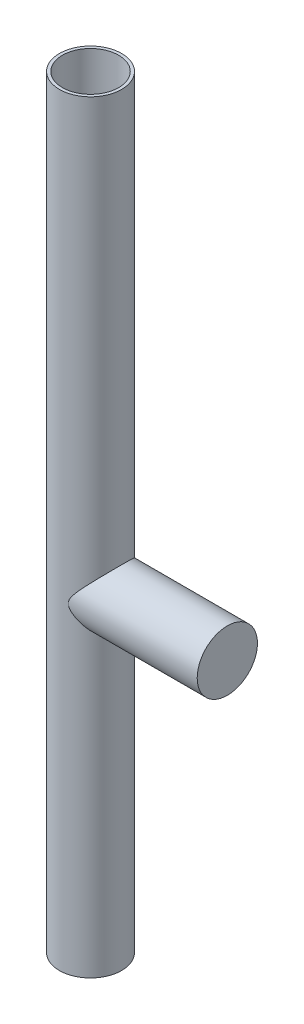
SolidWorks part; units mm, degrees
ref_plane "Front Plane" through (0, 0, 0) normal (0, 0, 1) x (1, 0, 0)
ref_plane "Top Plane" through (0, 0, 0) normal (0, 1, 0) x (1, 0, 0)
ref_plane "Right Plane" through (0, 0, 0) normal (1, 0, 0) x (0, 0, -1)
sketch "Sketch1" plane through (0, 0, 0) normal (0, 1, 0) x (1, 0, 0)
  circle A0 centre (0, 0) radius 7.75
  circle A1 centre (0, 0) radius 7
  dimension "D1" = 15.5
  dimension "D2" = 14
extrude "Boss-Extrude1" add sketch "Sketch1" along normal blind 160 and the other way blind 5
sketch "Sketch5" plane through (0, 0, 0) normal (1, 0, 0) x (0, 0, -1)
  circle A0 centre (0, 75) radius 7.5
  dimension "D1" = 15
extrude "Boss-Extrude3" add sketch "Sketch5" along normal blind 72.0622
sketch "Sketch7" plane through (0, 160, 0) normal (0, 1, 0) x (1, 0, 0)
  circle A0 centre (0, 0) radius 7
  circle A1 centre (0, 0) radius 7.75
extrude "Boss-Extrude5" add sketch "Sketch7" along normal blind 25
sketch "Sketch8" plane through (72.0622, 0, 0) normal (1, 0, 0) x (0, 0, -1)
  circle A0 centre (0, 75) radius 7.5
  circle A1 centre (0, 75) radius 7.5 construction
extrude "Cut-Extrude1" cut sketch "Sketch8" against normal blind 38
sketch "Sketch9" plane through (0, -5, 0) normal (0, -1, 0) x (1, 0, 0)
  circle A0 centre (0, 0) radius 7
  circle A1 centre (0, 0) radius 7 construction
extrude "Cut-Extrude2" cut sketch "Sketch9" against normal blind 105
